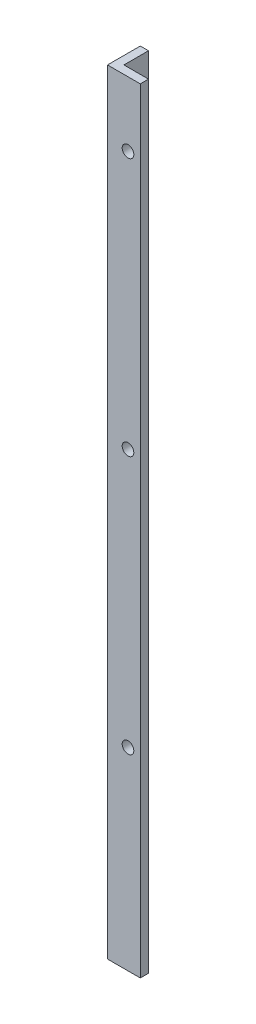
SolidWorks part; units mm, degrees
material "Alumina"
ref_plane "Front Plane" through (0, 0, 0) normal (0, 0, 1) x (1, 0, 0)
ref_plane "Top Plane" through (0, 0, 0) normal (0, 1, 0) x (1, 0, 0)
ref_plane "Right Plane" through (0, 0, 0) normal (1, 0, 0) x (0, 0, -1)
sketch "Sketch1" plane through (0, 0, 0) normal (0, 1, 0) x (1, 0, 0)
  line L0 (0, 0) -> (12.7, 0)
  line L1 (0, 0) -> (0, 12.7)
  line L2 (3.18, 3.18) -> (12.7, 3.18)
  line L3 (3.18, 3.18) -> (3.18, 12.7)
  line L4 (0, 12.7) -> (3.18, 12.7)
  line L5 (12.7, 0) -> (12.7, 3.18)
  dimension "D1" = 12.7
  dimension "D3" = 12.7
  dimension "D2" = 3.18
extrude "Boss-Extrude1" add sketch "Sketch1" along normal blind 300
sketch "Sketch2" plane through (0, 0, -3.18) normal (0, 0, -1) x (-1, 0, 0)
  line L0 (-7.94, 300) -> (-7.94, 0) construction
  line L3 (-12.7, 300) -> (-3.18, 300) construction
  line L4 (-12.7, 0) -> (-3.18, 0) construction
  circle A2 centre (-7.94, 275) radius 2.25
  circle A5 centre (-7.94, 175) radius 2.25
  circle A6 centre (-7.94, 75) radius 2.25
  dimension "D1" = 4.5
  dimension "D2" = 25
extrude "Cut-Extrude1" cut sketch "Sketch2" against normal blind 10
sketch "Sketch3" plane through (3.18, 0, 0) normal (1, 0, 0) x (0, 0, -1)
  line L0 (7.94, 300) -> (7.94, 0) construction
  line L1 (3.18, 300) -> (12.7, 300) construction
  line L2 (3.18, 0) -> (12.7, 0) construction
  circle A0 centre (7.94, 225) radius 2.25
  circle A2 centre (7.94, 125) radius 2.25
  circle A3 centre (7.94, 25) radius 2.25
  dimension "D1" = 4.5
  dimension "D2" = 75
extrude "Cut-Extrude2" cut sketch "Sketch3" against normal blind 10
sketch "Sketch4" plane through (0, 0, 0) normal (-1, 0, 0) x (0, 0, 1)
  circle A0 centre (-7.94, 253.6) radius 1.85
extrude "Cut-Extrude3" cut sketch "Sketch4" against normal through all
